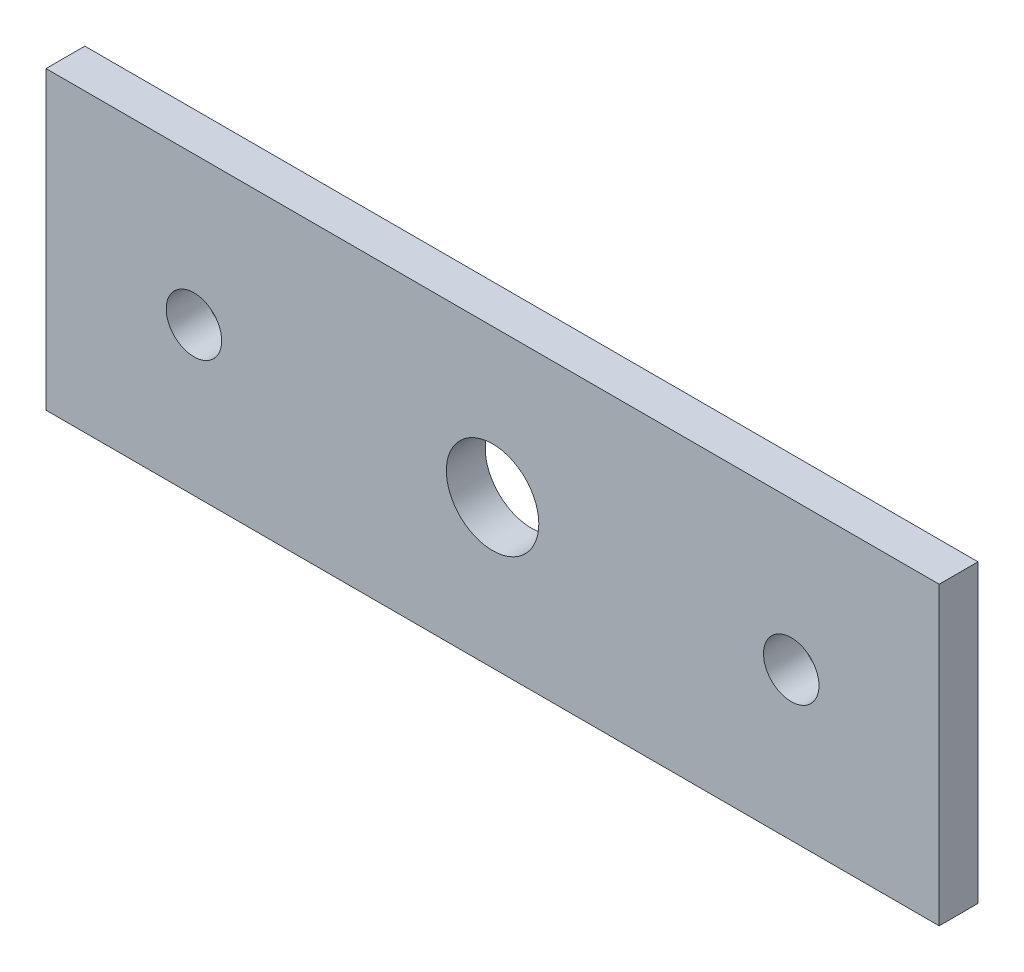
SolidWorks part; units mm, degrees
ref_plane "Plan de face" through (0, 0, 0) normal (0, 0, 1) x (1, 0, 0)
ref_plane "Plan de dessus" through (0, 0, 0) normal (0, 1, 0) x (1, 0, 0)
ref_plane "Plan de droite" through (0, 0, 0) normal (1, 0, 0) x (0, 0, -1)
sketch "Sketch1" plane through (0, 0, 0) normal (0, 0, 1) x (1, 0, 0)
  line L1 (-19.8825, 16.6713) -> (76.7175, 16.6713)
  line L2 (-19.8825, 16.6713) -> (-19.8825, -15.3287)
  line L3 (-19.8825, -15.3287) -> (76.7175, -15.3287)
  line L4 (76.7175, 16.6713) -> (76.7175, -15.3287)
  dimension "D1" = 32
  dimension "D2" = 96.6
extrude "Boss-Extrude1" add sketch "Sketch1" along normal blind 4.2
sketch "Sketch2" plane through (0, 0, 4.2) normal (0, 0, 1) x (1, 0, 0)
  line L0 (-19.8825, 16.6713) -> (-19.8825, -15.3287) construction
  line L1 (76.7175, 16.6713) -> (-19.8825, 16.6713) construction
  line L2 (76.7175, -15.3287) -> (76.7175, 16.6713) construction
  line L3 (-19.8825, -15.3287) -> (76.7175, -15.3287) construction
  circle A0 centre (-3.8825, 0.6713) radius 3
  circle A1 centre (60.7175, 0.6713) radius 3
  circle A2 centre (28.4175, 0.6713) radius 5
  point P12 (-19.8825, 0.6713)
  point P15 (24.554, -9.6396)
  dimension "D1" = 6
  dimension "D4" = 16
  dimension "D6" = 6
  dimension "D7" = 48.3
  dimension "D2" = 16
  dimension "D3" = 16
  dimension "D5" = 16
  dimension "D8" = 16
extrude "Cut-Extrude1" cut sketch "Sketch2" against normal through all
